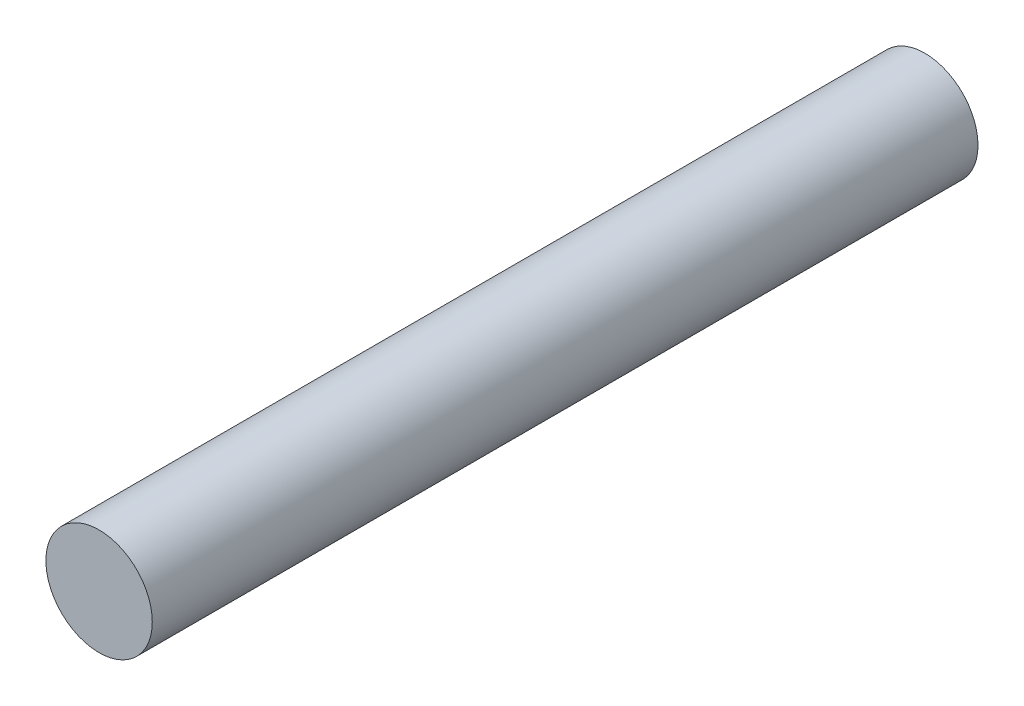
SolidWorks part; units mm, degrees
material "AISI 304"
ref_plane "Front Plane" through (0, 0, 0) normal (0, 0, 1) x (1, 0, 0)
ref_plane "Top Plane" through (0, 0, 0) normal (0, 1, 0) x (1, 0, 0)
ref_plane "Right Plane" through (0, 0, 0) normal (1, 0, 0) x (0, 0, -1)
sketch "Sketch1" plane through (0, 0, 0) normal (0, 0, 1) x (1, 0, 0)
  circle A0 centre (0, 0) radius 4
  dimension "D1" = 8
extrude "Boss-Extrude3" add sketch "Sketch1" along normal blind 62.1
